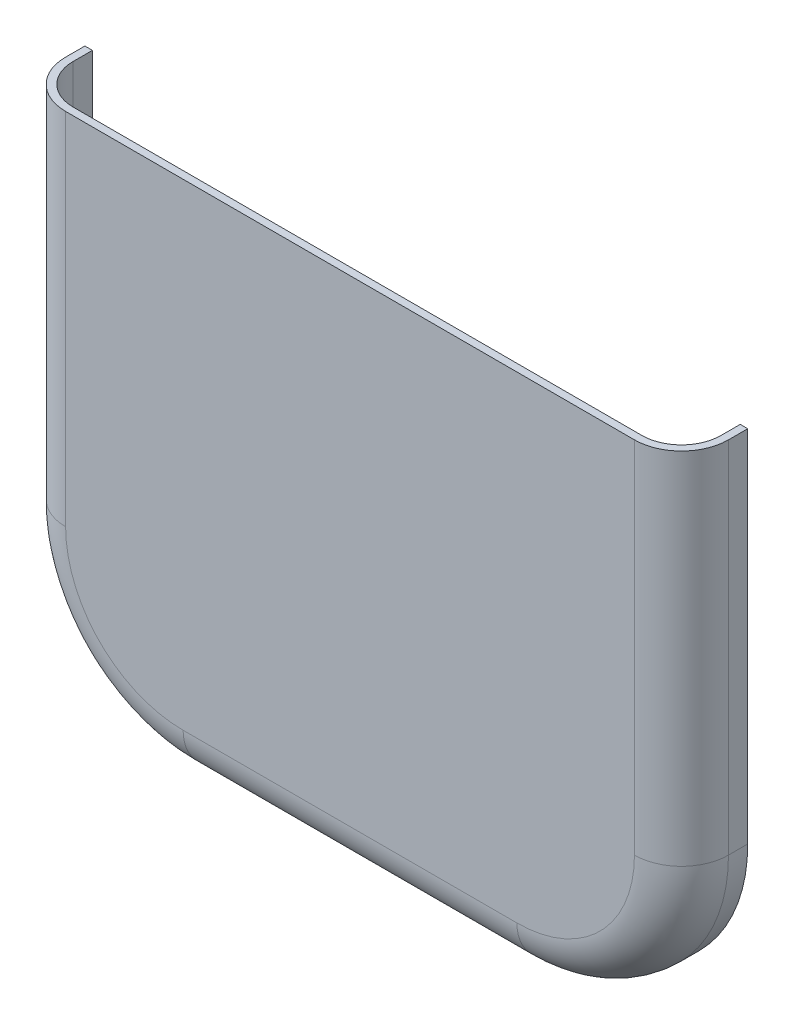
SolidWorks part; units mm, degrees
ref_plane "Front Plane" through (0, 0, 0) normal (0, 0, 1) x (1, 0, 0)
ref_plane "Top Plane" through (0, 0, 0) normal (0, 1, 0) x (1, 0, 0)
ref_plane "Right Plane" through (0, 0, 0) normal (1, 0, 0) x (0, 0, -1)
sketch "Sketch1" plane through (0, 0, 0) normal (0, 0, 1) x (1, 0, 0)
  line L1 (-15.748, 16.51) -> (15.748, 16.51)
  line L2 (-15.748, 16.51) -> (-15.748, -16.51)
  line L3 (-15.748, -16.51) -> (15.748, -16.51)
  line L4 (15.748, 16.51) -> (15.748, -16.51)
  dimension "D1" = 31.496
  dimension "D2" = 15.748
  dimension "D3" = 33.02
  dimension "D4" = 16.51
extrude "Boss-Extrude1" add sketch "Sketch1" along normal blind 7.1628
fillet "Fillet1" radius 8.89 2 edges at (-15.748, -16.51, 3.5814) (15.748, -16.51, 3.5814)
fillet "Fillet2" radius 2.54 10 edges at (-15.748, 4.445, 0) (-13.1442, -13.9062, 0) (0, -16.51, 0) (13.1442, -13.9062, 0) (15.748, 4.445, 7.1628) (13.1442, -13.9062, 7.1628) (0, -16.51, 7.1628) (-13.1442, -13.9062, 7.1628) (15.748, 4.445, 0) (-15.748, 4.445, 7.1628)
shell "Shell1" thickness 0.4064
sketch "Sketch2" plane through (0, 0, 0) normal (1, 0, 0) x (0, 0, -1)
  line L0 (-4.6228, 16.51) -> (-2.54, 16.51) construction
  line L1 (-3.5814, 16.51) -> (0.4052, 16.51)
  line L2 (-3.5814, 16.51) -> (-3.5814, -16.733)
  line L3 (-3.5814, -16.733) -> (0.4052, -16.733)
  line L4 (0.4052, 16.51) -> (0.4052, -16.733)
extrude "Cut-Extrude1" cut sketch "Sketch2" against normal mid plane 34.5948
sketch "Sketch3" plane through (0, 16.51, 0) normal (0, 1, 0) x (1, 0, 0)
  line L0 (15.3416, -3.5814) -> (15.748, -3.5814) construction
  line L1 (15.748, -4.6228) -> (15.748, -3.5814) construction
  line L2 (15.3416, -4.6228) -> (15.3416, -3.5814) construction
  line L3 (13.208, -6.7564) -> (-13.208, -6.7564) construction
  line L4 (13.208, -7.1628) -> (-13.208, -7.1628) construction
  line L5 (-15.3416, -3.5814) -> (-15.3416, -4.6228) construction
  line L6 (-15.748, -4.6228) -> (-15.748, -3.5814) construction
  line L7 (-15.748, -3.5814) -> (-15.3416, -3.5814) construction
  line L8 (15.3416, -3.5814) -> (15.748, -3.5814)
  line L9 (15.748, -4.6228) -> (15.748, -3.5814)
  line L10 (15.3416, -4.6228) -> (15.3416, -3.5814)
  line L11 (13.208, -6.7564) -> (-13.208, -6.7564)
  line L12 (13.208, -7.1628) -> (-13.208, -7.1628)
  line L13 (-15.3416, -3.5814) -> (-15.3416, -4.6228)
  line L14 (-15.748, -4.6228) -> (-15.748, -3.5814)
  line L15 (-15.748, -3.5814) -> (-15.3416, -3.5814)
  arc A0 (13.208, -7.1628) -> (15.748, -4.6228) centre (13.208, -4.6228) ccw construction
  arc A1 (13.208, -6.7564) -> (15.3416, -4.6228) centre (13.208, -4.6228) ccw construction
  arc A2 (-15.3416, -4.6228) -> (-13.208, -6.7564) centre (-13.208, -4.6228) ccw construction
  arc A3 (-15.748, -4.6228) -> (-13.208, -7.1628) centre (-13.208, -4.6228) ccw construction
  arc A4 (13.208, -7.1628) -> (15.748, -4.6228) centre (13.208, -4.6228) ccw
  arc A5 (13.208, -6.7564) -> (15.3416, -4.6228) centre (13.208, -4.6228) ccw
  arc A6 (-15.3416, -4.6228) -> (-13.208, -6.7564) centre (-13.208, -4.6228) ccw
  arc A7 (-15.748, -4.6228) -> (-13.208, -7.1628) centre (-13.208, -4.6228) ccw
extrude "Boss-Extrude2" add sketch "Sketch3" along normal blind 1.016
sketch "Sketch5" plane through (0, 17.526, 0) normal (0, 1, 0) x (1, 0, 0)
  line L1 (-15.3416, -3.5814) -> (-15.2908, -3.5814)
  line L2 (-15.3416, -3.5814) -> (-15.3416, -3.8862)
  line L3 (-15.3416, -3.8862) -> (-15.0016, -3.8862)
  line L10 (-15.2509, -2.8204) -> (-14.9465, -2.8364)
  line L11 (-15.2908, -3.5814) -> (-15.2509, -2.8204)
  line L17 (-15.5448, -3.3782) -> (-15.2802, -3.3782) construction
  line L18 (-15.5448, -3.3782) -> (-15.5448, -4.0894) construction
  line L19 (-15.5448, -4.0894) -> (-14.5929, -4.0894) construction
  line L20 (-14.5929, -4.0894) -> (-14.512, -2.6557) construction
  line L21 (-15.3416, -3.5814) -> (-15.0873, -3.5814) construction
  line L22 (-15.2802, -3.3782) -> (-15.2403, -2.6175) construction
  line L23 (-14.9465, -2.8364) -> (-15.0016, -3.8862)
  line L24 (-15.3416, -3.8862) -> (-14.7849, -3.8862) construction
  line L25 (-15.048, -2.8311) -> (-14.7264, -2.8479) construction
  line L27 (-15.0873, -3.5814) -> (-15.048, -2.8311) construction
  line L28 (-15.2403, -2.6175) -> (-14.512, -2.6557) construction
  line L29 (-14.7849, -3.8862) -> (-14.7264, -2.8479) construction
  dimension "D1" = 0.3048
  dimension "D2" = 0.3048
  dimension "D3" = 0.2032
  dimension "D4" = 3
  dimension "D5" = 0.762
  dimension "D6" = 0.0508
sketch "Sketch6" plane through (-0.1762, 0, 3.3618) normal (0.0523, 0, -0.9986) x (-0.9986, 0, -0.0523)
  line L1 (-3.0001, -16.9729) -> (-23.5738, -16.9729)
  line L2 (-3.0001, -16.9729) -> (-3.0001, 18.5814)
  line L3 (-3.0001, 18.5814) -> (-23.5738, 18.5814)
  line L4 (-23.5738, -16.9729) -> (-23.5738, 18.5814)
  dimension "D1" = 18.542
extrude "Cut-Extrude2" cut sketch "Sketch6" against normal up to surface (2.5708 mm away)
sketch "Sketch7" plane through (-0.1762, 0, 3.3618) normal (-0.0523, 0, 0.9986) x (0.9986, 0, 0.0523)
  line L1 (3.0001, -16.51) -> (24.1436, -16.51)
  line L2 (3.0001, -16.51) -> (3.0001, 19.6867)
  line L3 (3.0001, 19.6867) -> (24.1436, 19.6867)
  line L4 (24.1436, -16.51) -> (24.1436, 19.6867)
extrude "Cut-Extrude3" cut sketch "Sketch7" against normal blind 2.54
ref_plane "Plane2" through (2.996, 0, 0.157) normal (0.9986, 0, 0.0523) x (0.0523, 0, -0.9986)
ref_plane "Plane3" through (2.6288, 0, 0) normal (1, 0, 0) x (0, 0, -1)
mirror "Mirror5" about plane through (2.6288, 0, 0) normal (1, 0, 0)
sketch "Sketch8" plane through (0, 0, 7.1628) normal (0, 0, 1) x (1, 0, 0)
  line L0 (12.1689, -16.51) -> (-6.858, -16.51) construction
  line L5 (-19.6617, 14.986) -> (24.5131, 14.986)
  line L6 (-19.6617, 14.986) -> (-19.6617, 24.3723)
  line L7 (-19.6617, 24.3723) -> (24.5131, 24.3723)
  line L8 (24.5131, 14.986) -> (24.5131, 24.3723)
  point P0 (-15.748, 17.526)
  dimension "D1" = 31.496
extrude "Cut-Extrude4" cut sketch "Sketch8" against normal through all
sketch "Sketch9" plane through (0, 0, 7.1628) normal (0, 0, 1) x (1, 0, 0)
  line L1 (-15.748, 14.986) -> (2.159, 14.986)
  line L2 (-15.748, 14.986) -> (-15.748, -17.8909)
  line L3 (-15.748, -17.8909) -> (2.159, -17.8909)
  line L4 (2.159, 14.986) -> (2.159, -17.8909)
  dimension "D1" = 17.907
extrude "Cut-Extrude5" cut sketch "Sketch9" against normal through all flip side to cut
mirror "Mirror6" about plane through (2.159, 14.986, 3.5814) normal (1, 0, 0) of bodies 116
sketch "Sketch10" plane through (0, 0, 7.1628) normal (0, 0, 1) x (1, 0, 0)
  line L0 (20.066, -7.62) -> (20.066, 14.986) construction
  line L1 (-15.748, 14.986) -> (20.066, 14.986)
  line L2 (-15.748, 14.986) -> (-15.748, 11.811)
  line L3 (-15.748, 11.811) -> (20.066, 11.811)
  line L4 (20.066, 14.986) -> (20.066, 11.811)
  dimension "D1" = 3.175
extrude "Cut-Extrude6" cut sketch "Sketch10" against normal through all
